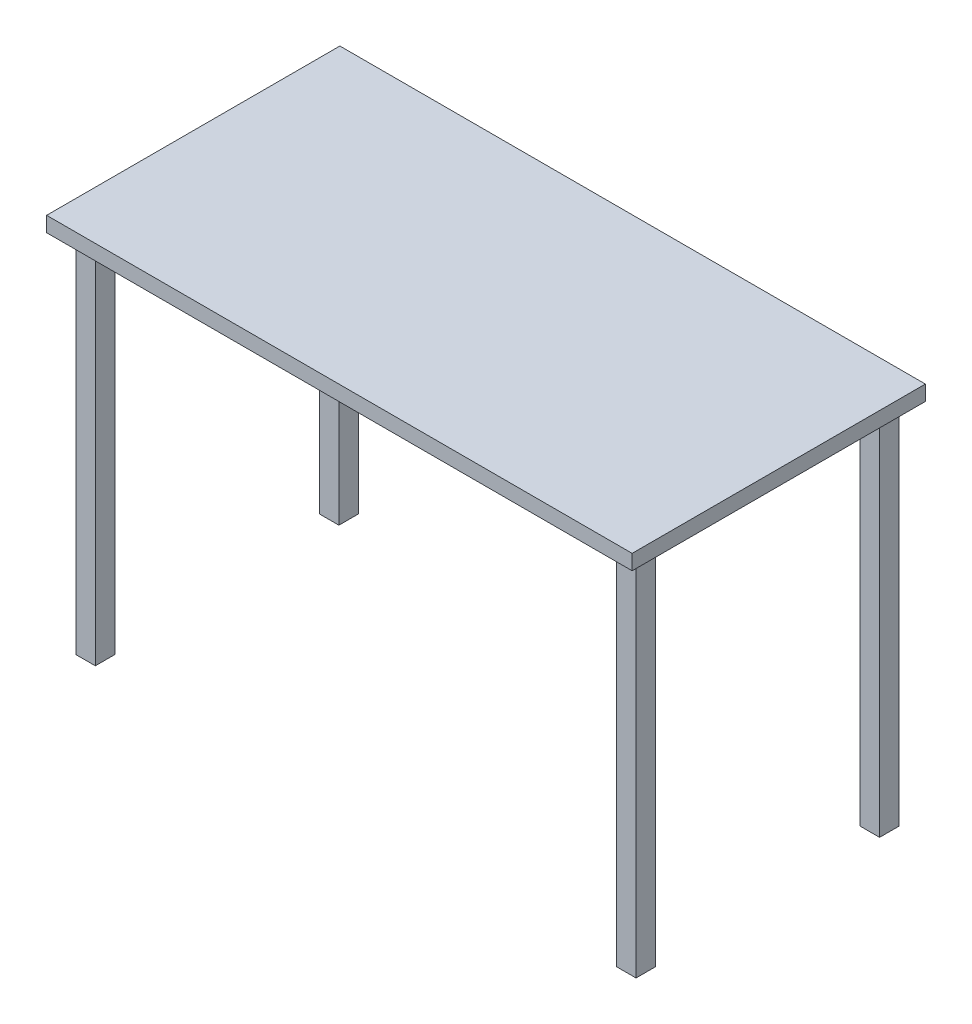
SolidWorks part; units mm, degrees
ref_plane "Alzado" through (0, 0, 0) normal (0, 0, 1) x (1, 0, 0)
ref_plane "Planta" through (0, 0, 0) normal (0, 1, 0) x (1, 0, 0)
ref_plane "Vista lateral" through (0, 0, 0) normal (1, 0, 0) x (0, 0, -1)
sketch "Croquis1" plane through (0, 0, 0) normal (0, 0, 1) x (1, 0, 0)
  line L0 (0, 0) -> (0, 80)
  line L1 (0, 80) -> (-58, 80)
  line L2 (-58, 80) -> (-58, 31.4551)
  line L3 (-58, 31.4551) -> (-67.5, 0)
  line L4 (-67.5, 0) -> (0, 0)
  dimension "D1" = 80
  dimension "D2" = 67.5
  dimension "D3" = 58
revolve "Revolución1" add sketch "Croquis1" angle 360 about L0
sketch "Croquis2" plane through (0, 80, 0) normal (0, 1, 0) x (1, 0, 0)
  circle A0 centre (0, 63.0252) radius 4.3246
  circle A1 centre (63.0252, 0) radius 4.3246
  circle A2 centre (0, -63.0252) radius 4.3246
  circle A3 centre (-63.0252, 0) radius 4.3246
  point P11 (0, 0)
  dimension "D1" = 4
extrude "Cortar-Extruir1" cut sketch "Croquis2" against normal blind 25 from offset 50 offset against normal yes
sketch "Croquis3" plane through (0, 0, 0) normal (0, -1, 0) x (1, 0, 0)
  line L1 (-601, 301) -> (601, 301)
  line L2 (-601, 301) -> (-601, -301)
  line L3 (-601, -301) -> (601, -301)
  line L4 (601, 301) -> (601, -301)
  line L5 (-601, 301) -> (601, -301) construction
  line L6 (-601, -301) -> (601, 301) construction
  point P0 (0, 0)
  dimension "D1" = 602
  dimension "D2" = 1202
extrude "Saliente-Extruir1" add sketch "Croquis3" along normal blind 31
sketch "Croquis4" plane through (0, -31, 0) normal (0, -1, 0) x (1, 0, 0)
  line L0 (601, 301) -> (-601, 301) construction
  line L1 (-571, 271) -> (-531, 271)
  line L2 (-571, 271) -> (-571, 231)
  line L3 (-571, 231) -> (-531, 231)
  line L4 (-531, 271) -> (-531, 231)
  line L5 (-601, 301) -> (-601, -301) construction
  line L6 (539, 271) -> (539, 231)
  line L7 (539, 271) -> (579, 271)
  line L8 (579, 271) -> (579, 231)
  line L9 (539, 231) -> (579, 231)
  line L10 (539, -229) -> (539, -269)
  line L11 (539, -229) -> (579, -229)
  line L12 (579, -229) -> (579, -269)
  line L13 (539, -269) -> (579, -269)
  line L14 (-571, -229) -> (-571, -269)
  line L15 (-571, -229) -> (-531, -229)
  line L16 (-531, -229) -> (-531, -269)
  line L17 (-571, -269) -> (-531, -269)
  dimension "D1" = 40
  dimension "D2" = 40
  dimension "D3" = 30
  dimension "D4" = 30
  dimension "D5" = 2
  dimension "D6" = 2
extrude "Saliente-Extruir2" add sketch "Croquis4" along normal blind 750
sketch "Croquis5" plane through (0, 0, 0) normal (0, 0, 1) x (1, 0, 0)
  line L0 (601, 0) -> (-601, 0) construction
  line L1 (75.1694, 0) -> (-94.0703, 0)
  line L2 (75.1694, 0) -> (75.1694, 94.1416)
  line L3 (75.1694, 94.1416) -> (-94.0703, 94.1416)
  line L4 (-94.0703, 0) -> (-94.0703, 94.1416)
extrude "Cortar-Extruir2" cut sketch "Croquis5" against normal through all and the other way through all
